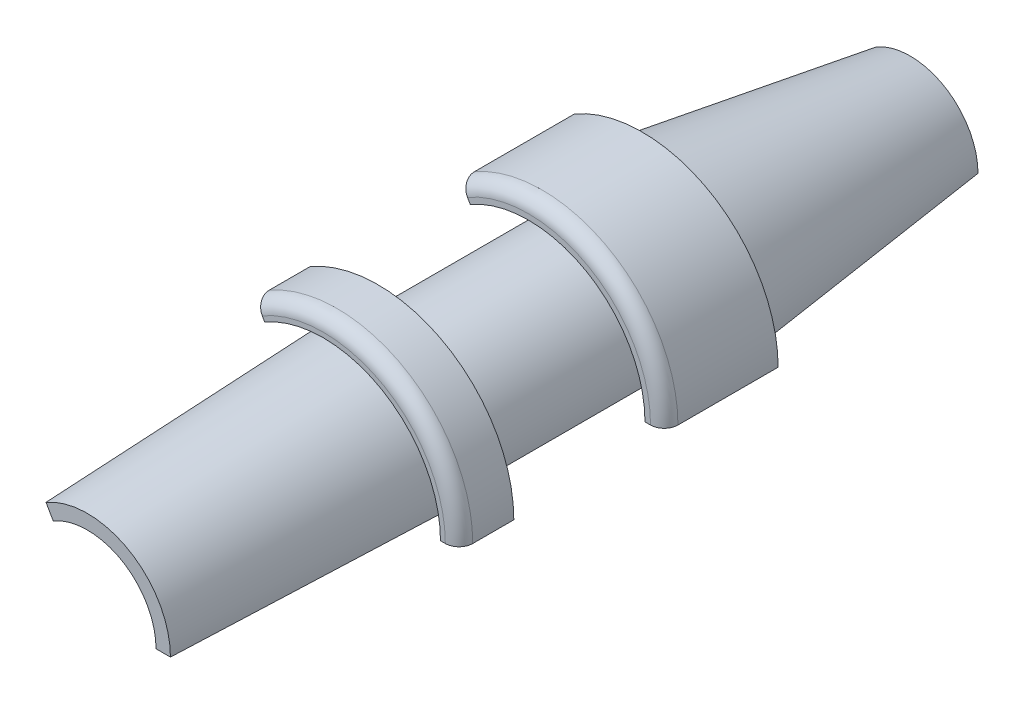
SolidWorks part; units mm, degrees
ref_plane "정면" through (0, 0, 0) normal (0, 0, 1) x (1, 0, 0)
ref_plane "윗면" through (0, 0, 0) normal (0, 1, 0) x (1, 0, 0)
ref_plane "우측면" through (0, 0, 0) normal (1, 0, 0) x (0, 0, -1)
sketch "스케치2" plane through (0, 0, 0) normal (0, 1, 0) x (1, 0, 0)
  line L0 (0, 0) -> (0, -30) construction
  line L1 (0, 0) -> (2.025, 0)
  line L2 (2.025, 0) -> (2.4712, 0)
  line L3 (2.4712, 0) -> (3.8962, -9.2849)
  line L4 (2.025, 0) -> (2.025, -5)
  line L5 (2.025, -5) -> (1.975, -5.05)
  line L6 (1.975, -5.05) -> (1.975, -5.95)
  line L7 (1.975, -5.95) -> (2.025, -6)
  line L8 (2.025, -6) -> (2.025, -30)
  line L9 (3.8962, -9.2849) -> (4.95, -9.7663)
  line L10 (4.95, -9.7663) -> (4.95, -13.9194)
  line L11 (4.95, -13.9194) -> (4.2477, -13.9194)
  line L12 (4.2477, -13.9194) -> (3.8962, -11.4906)
  line L13 (3.8962, -11.4906) -> (3.1142, -11.4906)
  line L14 (3.1142, -11.4906) -> (3.1142, -18.6018)
  line L15 (3.1142, -18.6018) -> (4.95, -19.4041)
  line L16 (4.95, -19.4041) -> (4.95, -21.4016)
  line L17 (4.95, -21.4016) -> (4.273, -21.4016)
  line L18 (4.273, -21.4016) -> (4.0958, -20.2531)
  line L19 (4.0958, -20.2531) -> (3.4465, -20)
  line L20 (3.4465, -20) -> (3.025, -30)
  line L21 (3.025, -30) -> (2.025, -30)
  line L22 (0, -30) -> (2.025, -30) construction
  dimension "D1" = 9.9
  dimension "D2" = 4.05
  dimension "D3" = 0.05
  dimension "D4" = 135
  dimension "D5" = 1
  dimension "D6" = 30
  dimension "D7" = 5
  dimension "D8" = 10
  dimension "D12" = 1
revolve "회전1" add sketch "스케치2" angle 120 about L0
sketch "스케치3" plane through (0, 0, 30) normal (0, 0, 1) x (1, 0, 0)
  circle A0 centre (0, 0) radius 2.5
  dimension "D1" = 5
extrude "컷-돌출1" cut sketch "스케치3" against normal blind 1.5
fillet "필렛1" radius 0.5 2 edges at (2.475, 4.2868, 13.9194) (2.475, 4.2868, 21.4016)
